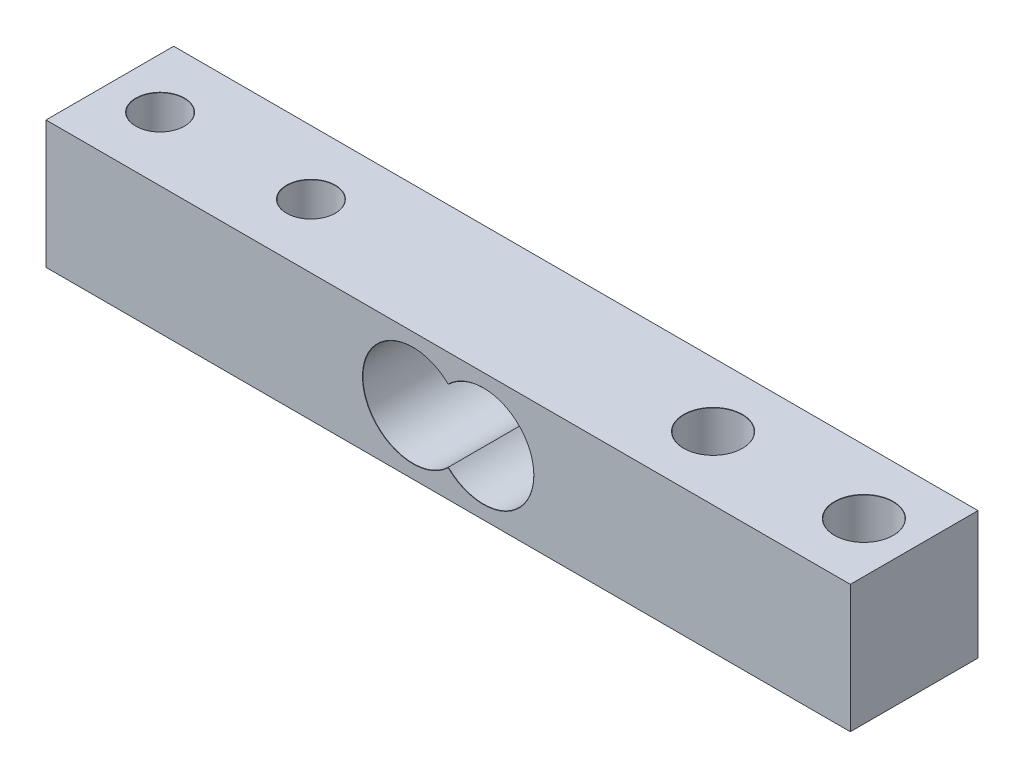
SolidWorks part; units mm, degrees
ref_plane "Front Plane" through (0, 0, 0) normal (0, 0, 1) x (1, 0, 0)
ref_plane "Top Plane" through (0, 0, 0) normal (0, 1, 0) x (1, 0, 0)
ref_plane "Right Plane" through (0, 0, 0) normal (1, 0, 0) x (0, 0, -1)
sketch "Sketch1" plane through (0, 0, 0) normal (0, 1, 0) x (1, 0, 0)
  line L1 (-40, -6.35) -> (40, -6.35)
  line L2 (-40, -6.35) -> (-40, 6.35)
  line L3 (-40, 6.35) -> (40, 6.35)
  line L4 (40, -6.35) -> (40, 6.35)
  line L5 (-40, -6.35) -> (40, 6.35) construction
  line L6 (-40, 6.35) -> (40, -6.35) construction
  point P0 (0, 0)
  dimension "D1" = 12.7
  dimension "D2" = 80
extrude "Boss-Extrude1" add sketch "Sketch1" along normal blind 12.7
hole_wizard "M4 Clearance Hole1" positions "Sketch2" profile "Sketch3" hole size "M4" standard "ANSI Metric" end condition through all
sketch "Sketch2" plane through (0, 12.7, 0) normal (0, 1, 0) x (1, 0, 0)
  line L0 (-35, 0) -> (-20, 0) construction
  line L1 (20, 0) -> (35, 0) construction
  line L3 (-20, 0) -> (20, 0) construction
  point P0 (-35, 0)
  point P2 (-20, 0)
  point P15 (0, 0)
  dimension "D1" = 15
  dimension "D2" = 40
sketch "Sketch3" plane through (-35, 12.7, 0) normal (1, 0, 0) x (0, 0, 1)
  line L0 (0, 0) -> (0, 12.7)
  line L1 (0, 12.7) -> (2.4, 12.7)
  line L2 (2.4, 12.7) -> (2.4, 0.021)
  line L3 (2.4, 0.021) -> (2.425, 0)
  line L5 (2.425, 0) -> (0, 0)
  line L6 (-2.4, 0.021) -> (-2.425, 0) construction
  line L11 (0, -6.35) -> (0, 107.95) construction
  dimension "Thru Hole Dia." = 4.8
  dimension "Thru Hole Depth" = 12.7
  dimension "Near C'Sink Dia." = 4.85
  dimension "Near C'Sink Angle" = 100
hole_wizard "M8 Clearance Hole1" positions "Sketch4" profile "Sketch5" hole size "M8" standard "ANSI Metric" end condition through all
sketch "Sketch4" plane through (0, 0, 6.35) normal (0, 0, 1) x (1, 0, 0)
  line L0 (-3.5, 6.35) -> (3.5, 6.35) construction
  line L2 (-40, 12.7) -> (-40, 0) construction
  point P0 (-3.5, 6.35)
  point P2 (3.5, 6.35)
  point P9 (0, 6.35)
  point P13 (-40, 6.35)
  dimension "D1" = 7
sketch "Sketch5" plane through (-3.5, 6.35, 6.35) normal (1, 0, 0) x (0, -1, 0)
  line L0 (0, 0) -> (0, 12.7)
  line L1 (0, 12.7) -> (5, 12.7)
  line L2 (5, 12.7) -> (5, 0.021)
  line L3 (5, 0.021) -> (5.025, 0)
  line L5 (5.025, 0) -> (0, 0)
  line L6 (-5, 0.021) -> (-5.025, 0) construction
  line L11 (0, -6.35) -> (0, 107.95) construction
  dimension "Thru Hole Dia." = 10
  dimension "Thru Hole Depth" = 12.7
  dimension "Near C'Sink Dia." = 10.05
  dimension "Near C'Sink Angle" = 100
hole_wizard "M5 Clearance Hole1" positions "Sketch6" profile "Sketch7" hole size "M5" standard "ANSI Metric" end condition through all
sketch "Sketch6" plane through (0, 12.7, 0) normal (0, 1, 0) x (1, 0, 0)
  line L0 (35, 0) -> (20, 0) construction
  line L1 (20, 0) -> (-20, 0) construction
  point P0 (35, 0)
  point P2 (20, 0)
  point P12 (0, 0)
  dimension "D1" = 15
sketch "Sketch7" plane through (35, 12.7, 0) normal (1, 0, 0) x (0, 0, 1)
  line L0 (0, 0) -> (0, 12.7)
  line L1 (0, 12.7) -> (2.9, 12.7)
  line L2 (2.9, 12.7) -> (2.9, 0.021)
  line L3 (2.9, 0.021) -> (2.925, 0)
  line L5 (2.925, 0) -> (0, 0)
  line L6 (-2.9, 0.021) -> (-2.925, 0) construction
  line L11 (0, -6.35) -> (0, 107.95) construction
  dimension "Thru Hole Dia." = 5.8
  dimension "Thru Hole Depth" = 12.7
  dimension "Near C'Sink Dia." = 5.85
  dimension "Near C'Sink Angle" = 100
